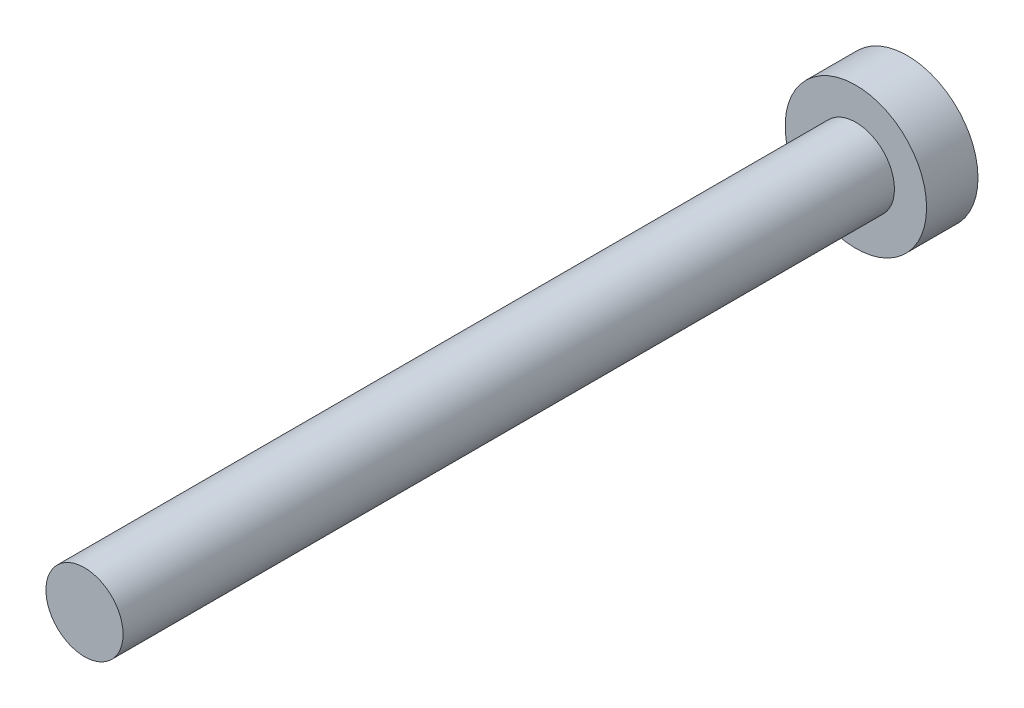
SolidWorks part; units mm, degrees
ref_plane "Plan de face" through (0, 0, 0) normal (0, 0, 1) x (1, 0, 0)
ref_plane "Plan de dessus" through (0, 0, 0) normal (0, 1, 0) x (1, 0, 0)
ref_plane "Plan de droite" through (0, 0, 0) normal (1, 0, 0) x (0, 0, -1)
sketch "Esquisse1" plane through (0, 0, 0) normal (0, 0, 1) x (1, 0, 0)
  circle A0 centre (0, 0) radius 2.75
  dimension "D1" = 5.5
extrude "Boss.-Extru.1" add sketch "Esquisse1" along normal blind 2
sketch "Esquisse2" plane through (0, 0, 2) normal (0, 0, 1) x (1, 0, 0)
  circle A0 centre (0, 0) radius 1.5
extrude "Boss.-Extru.2" add sketch "Esquisse2" along normal blind 30
